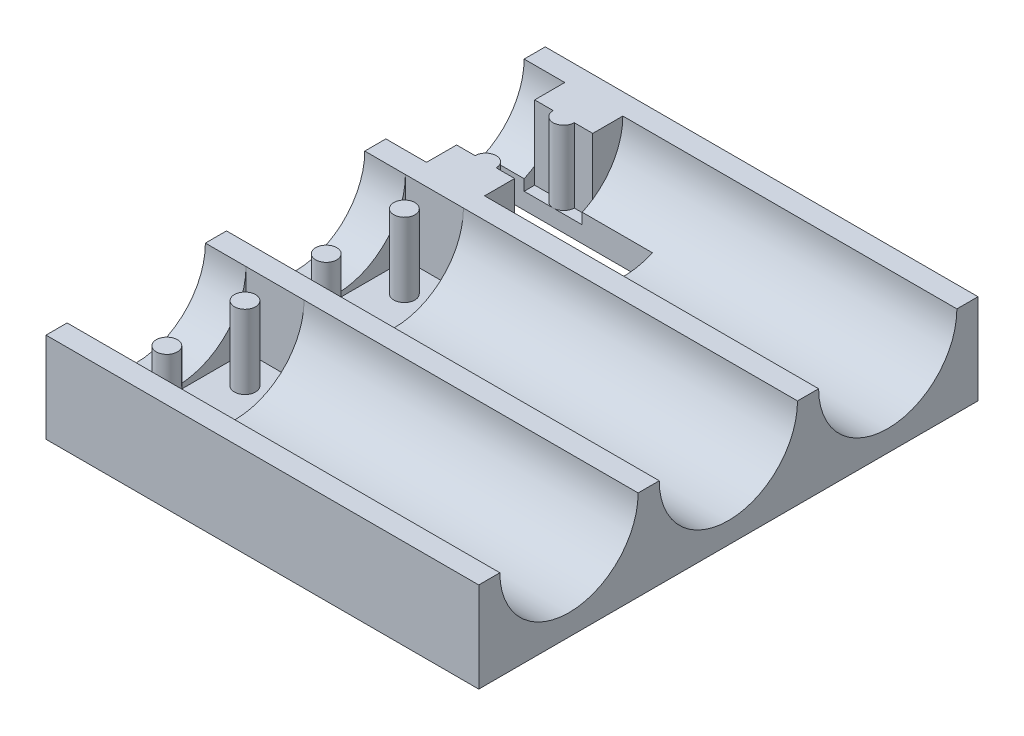
SolidWorks part; units mm, degrees
ref_plane "Front Plane" through (0, 0, 0) normal (0, 0, 1) x (1, 0, 0)
ref_plane "Top Plane" through (0, 0, 0) normal (0, 1, 0) x (1, 0, 0)
ref_plane "Right Plane" through (0, 0, 0) normal (1, 0, 0) x (0, 0, -1)
sketch "Sketch1" plane through (0, 0, 0) normal (1, 0, 0) x (0, 0, -1)
  line L0 (-8.55, 0) -> (-6.55, 0)
  line L1 (-6.55, 0) -> (6.55, 0) construction
  line L2 (6.55, 0) -> (8.55, 0)
  line L3 (-21.65, 0) -> (-8.55, 0) construction
  line L4 (8.55, 0) -> (21.65, 0) construction
  line L5 (-21.65, 0) -> (-23.65, 0)
  line L6 (-23.65, 0) -> (-23.65, -8.55)
  line L7 (-23.65, -8.55) -> (23.65, -8.55)
  line L8 (23.65, -8.55) -> (23.65, 0)
  line L9 (23.65, 0) -> (21.65, 0)
  line L10 (0, -6.55) -> (0, -8.55) construction
  arc A0 (-6.55, 0) -> (6.55, 0) centre (0, 0) ccw
  arc A1 (-21.65, 0) -> (-8.55, 0) centre (-15.1, 0) ccw
  arc A2 (8.55, 0) -> (21.65, 0) centre (15.1, 0) ccw
  dimension "D1" = 13.1
  dimension "D2" = 2
extrude "Boss-Extrude1" add sketch "Sketch1" along normal blind 41
sketch "Sketch2" plane through (0, 0, 0) normal (0, 1, 0) x (1, 0, 0)
  line L0 (6.6, -3.7) -> (6.6, 3.7) construction
  line L1 (5.6, -3.7) -> (5.6, 3.7) construction
  line L2 (0, -7.55) -> (41, -7.55) construction
  line L3 (0, -6.55) -> (0, -8.55) construction
  line L4 (41, -6.55) -> (41, -8.55) construction
  line L5 (0, 7.55) -> (41, 7.55) construction
  line L6 (0, 8.55) -> (0, 6.55) construction
  line L7 (41, 8.55) -> (41, 6.55) construction
  circle A2 centre (6.6, 3.7) radius 1
  circle A3 centre (6.6, -3.7) radius 1
  circle A4 centre (6.6, -11.4) radius 1
  circle A5 centre (6.6, -18.8) radius 1
  circle A6 centre (6.6, 18.8) radius 1
  circle A7 centre (6.6, 11.4) radius 1
  point P4 (6.6, 0)
  point P20 (0, 7.55)
  dimension "D2" = 2
  dimension "D1" = 5.6
  dimension "D3" = 7.4
extrude "Boss-Extrude2" add sketch "Sketch2" against normal up to next
sketch "Sketch4" plane through (0, 0, 0) normal (0, 1, 0) x (1, 0, 0)
  line L0 (41, -6.55) -> (0, -6.55) construction
  line L1 (3.85, -6.55) -> (9.35, -6.55)
  line L2 (3.85, -6.55) -> (3.85, 6.55)
  line L3 (3.85, 6.55) -> (9.35, 6.55)
  line L4 (9.35, -6.55) -> (9.35, 6.55)
  line L5 (41, 6.55) -> (0, 6.55) construction
  line L6 (6.6, -3.7) -> (6.6, 3.7) construction
  line L7 (9.35, 0) -> (3.85, 0) construction
  line L8 (0, -7.55) -> (41, -7.55) construction
  line L9 (0, -6.55) -> (0, -8.55) construction
  line L10 (41, -6.55) -> (41, -8.55) construction
  line L11 (0, 7.55) -> (41, 7.55) construction
  line L12 (0, 8.55) -> (0, 6.55) construction
  line L13 (41, 8.55) -> (41, 6.55) construction
  line L14 (3.85, -21.65) -> (9.35, -21.65)
  line L15 (9.35, -8.55) -> (9.35, -21.65)
  line L16 (3.85, -8.55) -> (9.35, -8.55)
  line L17 (3.85, -8.55) -> (3.85, -21.65)
  line L18 (3.85, 8.55) -> (9.35, 8.55)
  line L19 (9.35, 21.65) -> (9.35, 8.55)
  line L20 (3.85, 21.65) -> (9.35, 21.65)
  line L21 (3.85, 21.65) -> (3.85, 8.55)
  circle A0 centre (6.6, 3.7) radius 1 construction
  circle A1 centre (6.6, -3.7) radius 1 construction
  circle A2 centre (6.6, 3.7) radius 1
  circle A3 centre (6.6, -3.7) radius 1
  circle A4 centre (6.6, -11.4) radius 1
  circle A5 centre (6.6, -18.8) radius 1
  circle A6 centre (6.6, 11.4) radius 1
  circle A7 centre (6.6, 18.8) radius 1
  point P16 (6.6, 0)
  point P17 (6.6, 0)
  dimension "D1" = 5.5
extrude "Cut-Extrude1" cut sketch "Sketch4" against normal blind 7
sketch "Sketch5" plane through (0, -8.55, 0) normal (0, -1, 0) x (1, 0, 0)
  line L0 (0, 23.65) -> (0, 20.65)
  line L1 (-5.2552, 30.9052) -> (1, 30.9052)
  line L2 (-7.2552, 28.9052) -> (-7.2552, 22.65)
  line L3 (-5.2552, 20.65) -> (0, 20.65)
  line L12 (3, 28.9052) -> (3, 23.65)
  line L14 (0, 23.65) -> (3, 23.65)
  line L16 (0, 23.65) -> (-7.2552, 30.9052) construction
  line L17 (-3.0052, 28.9052) -> (-3.0052, 30.9052) construction
  line L18 (-1.4142, 25.0642) -> (0, 23.65) construction
  line L19 (0, 0) -> (41, 0) construction
  line L20 (41, 23.65) -> (41, -23.65) construction
  line L21 (-1.4142, -25.0642) -> (0, -23.65) construction
  line L22 (-3.0052, -28.9052) -> (-3.0052, -30.9052) construction
  line L23 (0, -23.65) -> (-7.2552, -30.9052) construction
  line L24 (0, -23.65) -> (3, -23.65)
  line L25 (3, -28.9052) -> (3, -23.65)
  line L26 (-5.2552, -20.65) -> (0, -20.65)
  line L27 (-7.2552, -28.9052) -> (-7.2552, -22.65)
  line L28 (-5.2552, -30.9052) -> (1, -30.9052)
  line L29 (0, -23.65) -> (0, -20.65)
  line L30 (20.5, 23.65) -> (20.5, -23.65) construction
  line L31 (41, 23.65) -> (0, 23.65) construction
  line L32 (41, -23.65) -> (0, -23.65) construction
  line L33 (41, -23.65) -> (48.2552, -30.9052) construction
  line L34 (44.0052, -28.9052) -> (44.0052, -30.9052) construction
  line L35 (42.4142, -25.0642) -> (41, -23.65) construction
  line L36 (42.4142, 25.0642) -> (41, 23.65) construction
  line L37 (44.0052, 28.9052) -> (44.0052, 30.9052) construction
  line L38 (41, 23.65) -> (48.2552, 30.9052) construction
  line L39 (41, -23.65) -> (41, -20.65)
  line L40 (46.2552, -30.9052) -> (40, -30.9052)
  line L41 (48.2552, -28.9052) -> (48.2552, -22.65)
  line L42 (46.2552, -20.65) -> (41, -20.65)
  line L43 (38, -28.9052) -> (38, -23.65)
  line L44 (41, -23.65) -> (38, -23.65)
  line L45 (41, 23.65) -> (38, 23.65)
  line L46 (38, 28.9052) -> (38, 23.65)
  line L47 (46.2552, 20.65) -> (41, 20.65)
  line L48 (48.2552, 28.9052) -> (48.2552, 22.65)
  line L49 (46.2552, 30.9052) -> (40, 30.9052)
  line L50 (41, 23.65) -> (41, 20.65)
  circle A0 centre (-3.0052, 26.6552) radius 2.25
  arc A1 (-7.2552, 22.65) -> (-5.2552, 20.65) centre (-5.2552, 22.65) ccw
  arc A2 (-5.2552, 30.9052) -> (-7.2552, 28.9052) centre (-5.2552, 28.9052) ccw
  arc A3 (1, 30.9052) -> (3, 28.9052) centre (1, 28.9052) cw
  arc A4 (1, -30.9052) -> (3, -28.9052) centre (1, -28.9052) ccw
  arc A5 (-5.2552, -30.9052) -> (-7.2552, -28.9052) centre (-5.2552, -28.9052) cw
  arc A6 (-7.2552, -22.65) -> (-5.2552, -20.65) centre (-5.2552, -22.65) cw
  circle A7 centre (-3.0052, -26.6552) radius 2.25
  circle A8 centre (44.0052, -26.6552) radius 2.25
  arc A9 (48.2552, -22.65) -> (46.2552, -20.65) centre (46.2552, -22.65) ccw
  arc A10 (46.2552, -30.9052) -> (48.2552, -28.9052) centre (46.2552, -28.9052) ccw
  arc A11 (40, -30.9052) -> (38, -28.9052) centre (40, -28.9052) cw
  arc A12 (40, 30.9052) -> (38, 28.9052) centre (40, 28.9052) ccw
  arc A13 (46.2552, 30.9052) -> (48.2552, 28.9052) centre (46.2552, 28.9052) cw
  arc A14 (48.2552, 22.65) -> (46.2552, 20.65) centre (46.2552, 22.65) cw
  circle A15 centre (44.0052, 26.6552) radius 2.25
  dimension "D1" = 4.5
  dimension "D4" = 2
  dimension "D5" = 2
  dimension "D2" = 3
  dimension "D3" = 2
extrude "Boss-Extrude3" add sketch "Sketch5" against normal blind 2
sketch "Sketch6" plane through (0, 0, 0) normal (0, 1, 0) x (1, 0, 0)
  line L0 (0, 0) -> (41, 0) construction
  line L1 (3.85, -3.7) -> (9.35, -3.7)
  line L2 (9.35, -3.7) -> (9.35, -6.55)
  line L3 (9.35, -6.55) -> (3.85, -6.55)
  line L4 (3.85, -6.55) -> (3.85, -3.7)
  line L5 (7.6, -3.7) -> (5.6, -3.7) construction
  line L6 (7.6, 3.7) -> (5.6, 3.7) construction
  line L7 (3.85, 6.55) -> (3.85, 3.7)
  line L8 (9.35, 6.55) -> (3.85, 6.55)
  line L9 (9.35, 3.7) -> (9.35, 6.55)
  line L10 (3.85, 3.7) -> (9.35, 3.7)
  line L11 (0, -7.55) -> (41, -7.55) construction
  line L12 (0, 7.55) -> (41, 7.55) construction
  line L13 (0, -6.55) -> (0, -8.55) construction
  line L14 (0, 8.55) -> (0, 6.55) construction
  line L15 (41, 8.55) -> (41, 6.55) construction
  line L16 (41, -6.55) -> (41, 6.55) construction
  line L17 (41, -6.55) -> (41, -8.55) construction
  line L18 (9.35, -6.55) -> (9.35, 6.55) construction
  line L19 (5.6, -3.7) -> (7.6, -3.7) construction
  line L20 (5.6, -11.4) -> (7.6, -11.4) construction
  line L21 (7.6, -18.8) -> (5.6, -18.8) construction
  line L22 (7.6, -11.4) -> (5.6, -11.4) construction
  line L23 (3.85, -18.8) -> (9.35, -18.8)
  line L24 (9.35, -18.8) -> (9.35, -21.65)
  line L25 (9.35, -21.65) -> (3.85, -21.65)
  line L26 (3.85, -21.65) -> (3.85, -18.8)
  line L27 (3.85, -8.55) -> (3.85, -11.4)
  line L28 (9.35, -8.55) -> (3.85, -8.55)
  line L29 (9.35, -11.4) -> (9.35, -8.55)
  line L30 (3.85, -11.4) -> (9.35, -11.4)
  line L31 (5.6, 18.8) -> (7.6, 18.8) construction
  line L32 (7.6, 11.4) -> (5.6, 11.4) construction
  line L33 (7.6, 18.8) -> (5.6, 18.8) construction
  line L34 (3.85, 11.4) -> (9.35, 11.4)
  line L35 (9.35, 11.4) -> (9.35, 8.55)
  line L36 (9.35, 8.55) -> (3.85, 8.55)
  line L37 (3.85, 8.55) -> (3.85, 11.4)
  line L38 (3.85, 21.65) -> (3.85, 18.8)
  line L39 (9.35, 21.65) -> (3.85, 21.65)
  line L40 (9.35, 18.8) -> (9.35, 21.65)
  line L41 (3.85, 18.8) -> (9.35, 18.8)
  circle A0 centre (6.6, -3.7) radius 1 construction
  circle A1 centre (6.6, -3.7) radius 1 construction
extrude "Boss-Extrude4" add sketch "Sketch6" against normal up to surface (7 mm away) up to face at (6.6, -7, -19.8)
sketch "Sketch7" plane through (0, 0, 0) normal (0, 1, 0) x (1, 0, 0)
  line L0 (5.6, 3.7) -> (3.85, 3.7)
  line L1 (3.85, 3.7) -> (3.85, 6.55)
  line L2 (3.85, 6.55) -> (9.35, 6.55)
  line L3 (9.35, 6.55) -> (9.35, 3.7)
  line L4 (7.6, 3.7) -> (9.35, 3.7) construction
  line L5 (7.6, 3.7) -> (9.35, 3.7)
  line L6 (0, 0) -> (41, 0) construction
  line L7 (41, -6.55) -> (41, 6.55) construction
  line L8 (7.6, -3.7) -> (9.35, -3.7)
  line L9 (9.35, -6.55) -> (9.35, -3.7)
  line L10 (3.85, -6.55) -> (9.35, -6.55)
  line L11 (3.85, -3.7) -> (3.85, -6.55)
  line L12 (5.6, -3.7) -> (3.85, -3.7)
  line L13 (0, 7.55) -> (41, 7.55) construction
  line L14 (0, 8.55) -> (0, 6.55) construction
  line L15 (41, 8.55) -> (41, 6.55) construction
  line L26 (0, -7.55) -> (41, -7.55) construction
  line L27 (0, -6.55) -> (0, -8.55) construction
  line L28 (41, -6.55) -> (41, -8.55) construction
  line L29 (5.6, -11.4) -> (3.85, -11.4)
  line L30 (3.85, -11.4) -> (3.85, -8.55)
  line L31 (3.85, -8.55) -> (9.35, -8.55)
  line L32 (9.35, -8.55) -> (9.35, -11.4)
  line L33 (7.6, -11.4) -> (9.35, -11.4)
  line L34 (7.6, -18.8) -> (9.35, -18.8)
  line L35 (9.35, -21.65) -> (9.35, -18.8)
  line L36 (3.85, -21.65) -> (9.35, -21.65)
  line L37 (3.85, -18.8) -> (3.85, -21.65)
  line L38 (5.6, -18.8) -> (3.85, -18.8)
  arc A0 (7.6, 3.7) -> (5.6, 3.7) centre (6.6, 3.7) ccw
  arc A1 (5.6, 3.7) -> (7.6, 3.7) centre (6.6, 3.7) ccw construction
  arc A2 (7.6, -3.7) -> (5.6, -3.7) centre (6.6, -3.7) cw
  arc A5 (7.6, -11.4) -> (5.6, -11.4) centre (6.6, -11.4) ccw
  arc A6 (7.6, -18.8) -> (5.6, -18.8) centre (6.6, -18.8) cw
extrude "Cut-Extrude2" cut sketch "Sketch7" against normal up to surface (7 mm away) up to face at (6.6, -7, -15.1)
sketch "Sketch8" plane through (0, -6.55, 0) normal (0, 1, 0) x (1, 0, 0)
  line L1 (0, -23.65) -> (41, -23.65)
  line L2 (0, -23.65) -> (0, 23.65)
  line L3 (0, 23.65) -> (41, 23.65)
  line L4 (41, -23.65) -> (41, 23.65)
  line L5 (52.6282, -33.2148) -> (-16.7146, -33.2148)
  line L6 (52.6282, -33.2148) -> (52.6282, 38.2719)
  line L7 (52.6282, 38.2719) -> (-16.7146, 38.2719)
  line L8 (-16.7146, -33.2148) -> (-16.7146, 38.2719)
extrude "Cut-Extrude3" cut sketch "Sketch8" against normal through all
sketch "Sketch9" plane through (0, -7, 0) normal (0, 1, 0) x (1, 0, 0)
  line L1 (0, 12.4) -> (16, 12.4)
  line L2 (0, 12.4) -> (0, 17.8)
  line L3 (0, 17.8) -> (16, 17.8)
  line L4 (16, 12.4) -> (16, 17.8)
  line L5 (0, 21.65) -> (0, 8.55) construction
  arc A2 (5.6, 18.8) -> (7.6, 18.8) centre (6.6, 18.8) ccw construction
  arc A3 (7.6, 11.4) -> (5.6, 11.4) centre (6.6, 11.4) ccw construction
  point P4 (21.8035, -12.4)
  dimension "D1" = 16
extrude "Cut-Extrude4" cut sketch "Sketch9" against normal through all both and the other way through all
